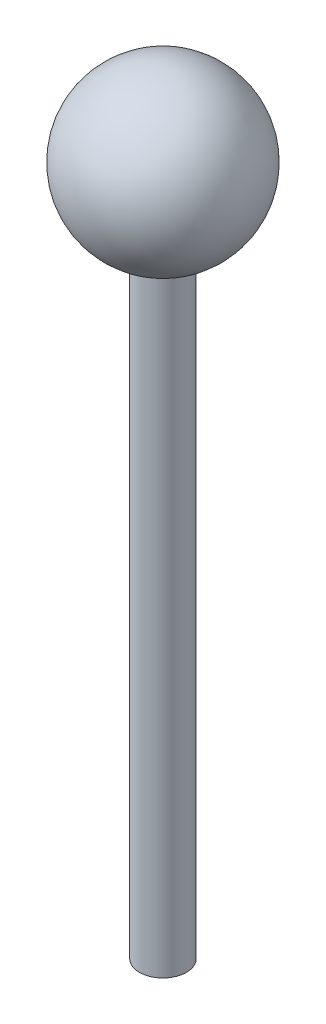
SolidWorks part; units mm, degrees
ref_plane "Front Plane" through (0, 0, 0) normal (0, 0, 1) x (1, 0, 0)
ref_plane "Top Plane" through (0, 0, 0) normal (0, 1, 0) x (1, 0, 0)
ref_plane "Right Plane" through (0, 0, 0) normal (1, 0, 0) x (0, 0, -1)
sketch "Sketch1" plane through (0, 0, 0) normal (0, 0, 1) x (1, 0, 0)
  line L0 (0, -1000) -> (0, 49000) construction
  line L2 (5, -16.7705) -> (5, -146.7705)
  line L3 (5, -146.7705) -> (0, -146.7705)
  line L4 (0, -146.7705) -> (0, -1.75)
  line L5 (0, 17.5) -> (0, -1.75)
  arc A0 (5, -16.7705) -> (0, 17.5) centre (0, 0) ccw
  dimension "D1" = 35
  dimension "D3" = 5
  dimension "D2" = 130
revolve "Revolve1" add sketch "Sketch1" angle 360 about L0
